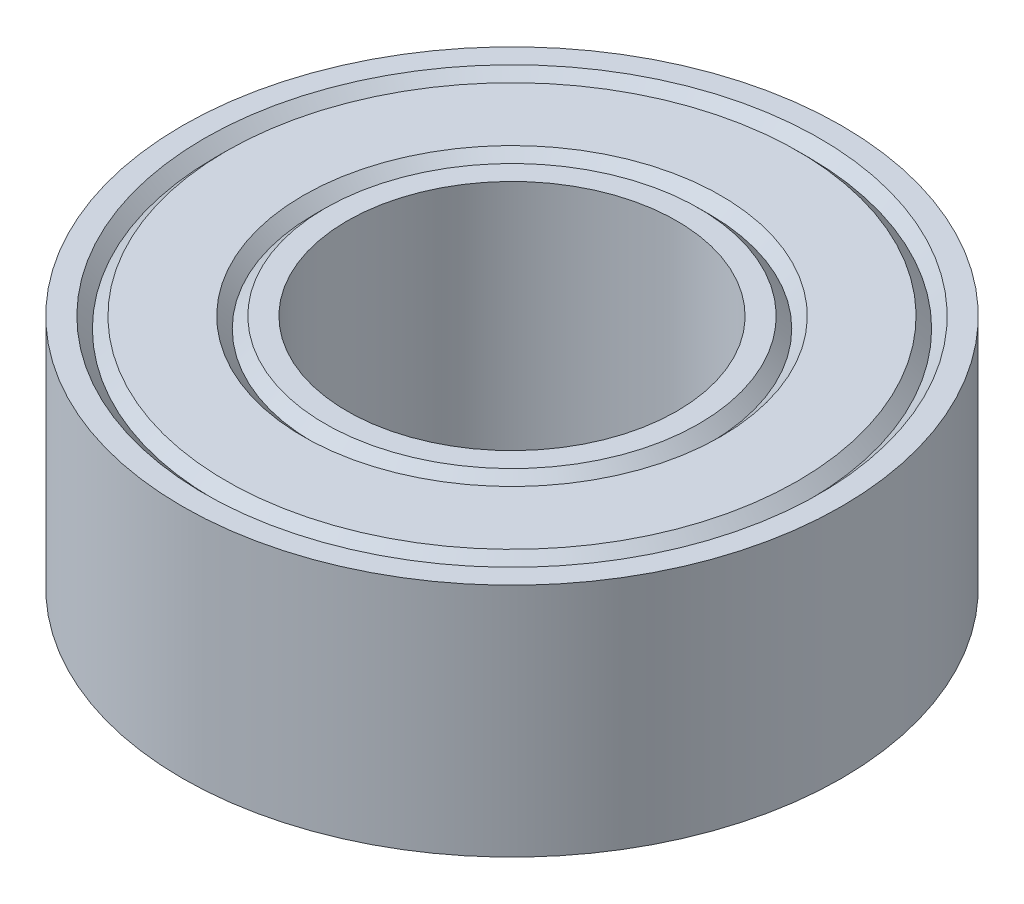
SolidWorks part; units mm, degrees
ref_plane "Front Plane" through (0, 0, 0) normal (0, 0, 1) x (1, 0, 0)
ref_plane "Top Plane" through (0, 0, 0) normal (0, 1, 0) x (1, 0, 0)
ref_plane "Right Plane" through (0, 0, 0) normal (1, 0, 0) x (0, 0, -1)
sketch "Sketch1" plane through (0, 0, 0) normal (0, 0, 1) x (1, 0, 0)
  line L0 (0, 2.5) -> (0, -2.5) construction
  line L1 (-3.5, 2.5) -> (-3.9667, 2.5)
  line L2 (-3.5, 2.5) -> (-3.5, -2.5)
  line L3 (-3.5, -2.5) -> (-3.9667, -2.5)
  line L4 (-7, 2.5) -> (-7, -2.5)
  line L5 (-6.5333, 2.5) -> (-6.3, 2.2667)
  line L6 (-6.3, 2.2667) -> (-6.0667, 2.5)
  line L7 (-4.4333, 2.5) -> (-4.2, 2.2667)
  line L8 (-4.2, 2.2667) -> (-3.9667, 2.5)
  line L9 (-6.5333, -2.5) -> (-6.3, -2.2667)
  line L10 (-6.3, -2.2667) -> (-6.0667, -2.5)
  line L11 (-4.4333, -2.5) -> (-4.2, -2.2667)
  line L12 (-4.2, -2.2667) -> (-3.9667, -2.5)
  line L13 (-4.4333, -2.5) -> (-6.0667, -2.5)
  line L14 (-6.5333, -2.5) -> (-7, -2.5)
  line L15 (-6.5333, 2.5) -> (-7, 2.5)
  line L16 (-4.4333, 2.5) -> (-6.0667, 2.5)
  line L17 (-6.3, 2.2667) -> (-4.2, 2.2667) construction
  line L18 (-6.3, 2.2667) -> (-6.3, -2.2667) construction
  line L19 (-4.2, -2.2667) -> (-6.3, -2.2667) construction
  line L20 (-4.2, 2.2667) -> (-4.2, -2.2667) construction
  line L21 (-6.3, 0) -> (-5.6, 0) construction
  line L22 (-3.9667, 2.5) -> (-4.4333, 2.5) construction
  line L23 (-5.6, 0) -> (-4.9, 0) construction
  line L24 (-6.3, 0) -> (-7, 0) construction
  line L25 (-4.9, 0) -> (-4.2, 0) construction
  line L26 (-4.2, 0) -> (-3.5, 0) construction
  dimension "D1" = 5
  dimension "D2" = 7
  dimension "D3" = 14
revolve "Revolve1" add sketch "Sketch1" angle 360 about L0
